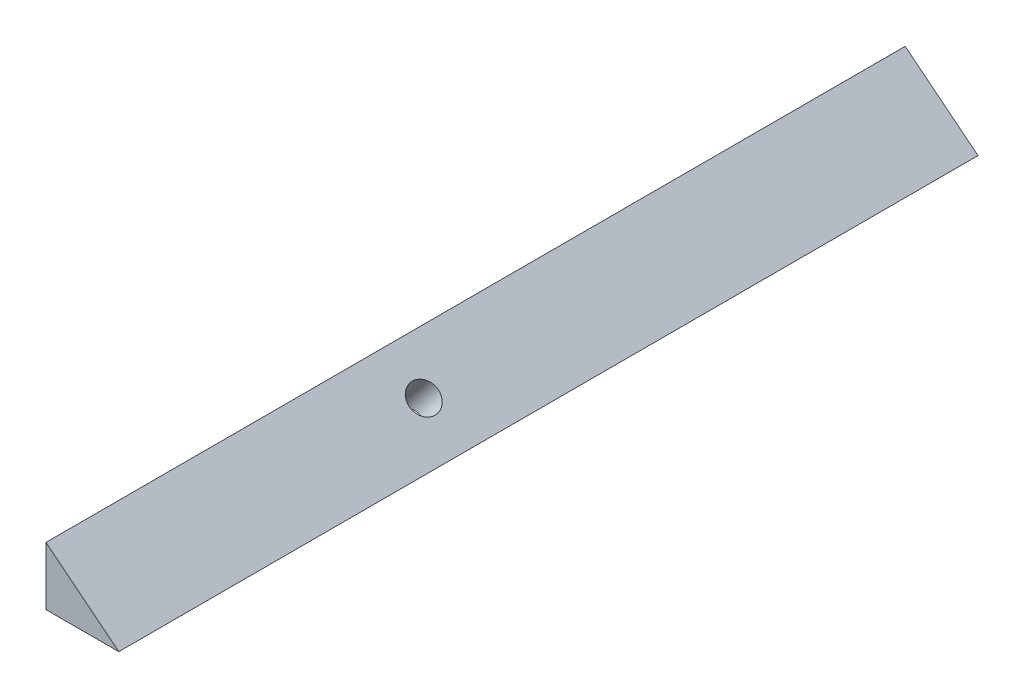
SolidWorks part; units mm, degrees
ref_plane "Front Plane" through (0, 0, 0) normal (0, 0, 1) x (1, 0, 0)
ref_plane "Top Plane" through (0, 0, 0) normal (0, 1, 0) x (1, 0, 0)
ref_plane "Right Plane" through (0, 0, 0) normal (1, 0, 0) x (0, 0, -1)
sketch "Sketch1" plane through (0, 0, 0) normal (0, 0, 1) x (1, 0, 0)
  line L0 (63.5, 0) -> (0, 50.8)
  line L1 (0, 0) -> (63.5, 0)
  line L2 (0, 0) -> (0, 50.8)
  line L3 (0, 50.8) -> (63.5, 50.8)
  line L4 (63.5, 0) -> (63.5, 50.8)
  dimension "D1" = 50.8
  dimension "D2" = 63.5
extrude "Boss-Extrude1" add sketch "Sketch1" against normal blind 38.1 contours L2 L1 L0
sketch "Sketch2" plane through (24.7805, 30.9756, 0) normal (0.6247, 0.7809, 0) x (0.7809, -0.6247, 0)
  line L0 (49.5852, 0) -> (-31.7345, 0) construction
  circle A0 centre (7.9717, 19.05) radius 12.7
  dimension "D1" = 25.4
  dimension "D2" = 19.05
extrude "Cut-Extrude1" cut sketch "Sketch2" against normal through all
sketch "Sketch3" plane through (0, 0, 0) normal (0, 0, 1) x (1, 0, 0)
  line L0 (0, 50.8) -> (0, 0)
  line L1 (0, 0) -> (63.5, 0)
  line L2 (63.5, 0) -> (0, 50.8)
extrude "Boss-Extrude2" add sketch "Sketch3" along normal blind 279.4
sketch "Sketch4" plane through (0, 0, -38.1) normal (0, 0, -1) x (-1, 0, 0)
  line L0 (0, 50.8) -> (-63.5, 0)
  line L1 (-63.5, 0) -> (0, 0)
  line L2 (0, 0) -> (0, 50.8)
extrude "Boss-Extrude3" add sketch "Sketch4" along normal blind 431.8
